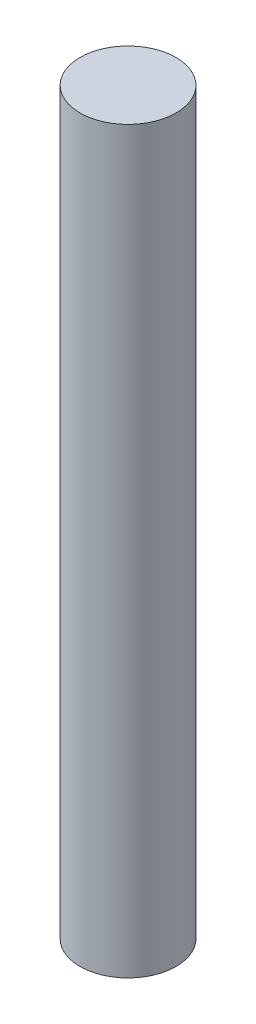
SolidWorks part; units mm, degrees
ref_plane "Front Plane" through (0, 0, 0) normal (0, 0, 1) x (1, 0, 0)
ref_plane "Top Plane" through (0, 0, 0) normal (0, 1, 0) x (1, 0, 0)
ref_plane "Right Plane" through (0, 0, 0) normal (1, 0, 0) x (0, 0, -1)
sketch "Sketch1" plane through (0, 0, 0) normal (0, 1, 0) x (1, 0, 0)
  circle A0 centre (0, 0) radius 2.4765
  dimension "D1" = 4.953
extrude "Boss-Extrude1" add sketch "Sketch1" along normal blind 38.1
